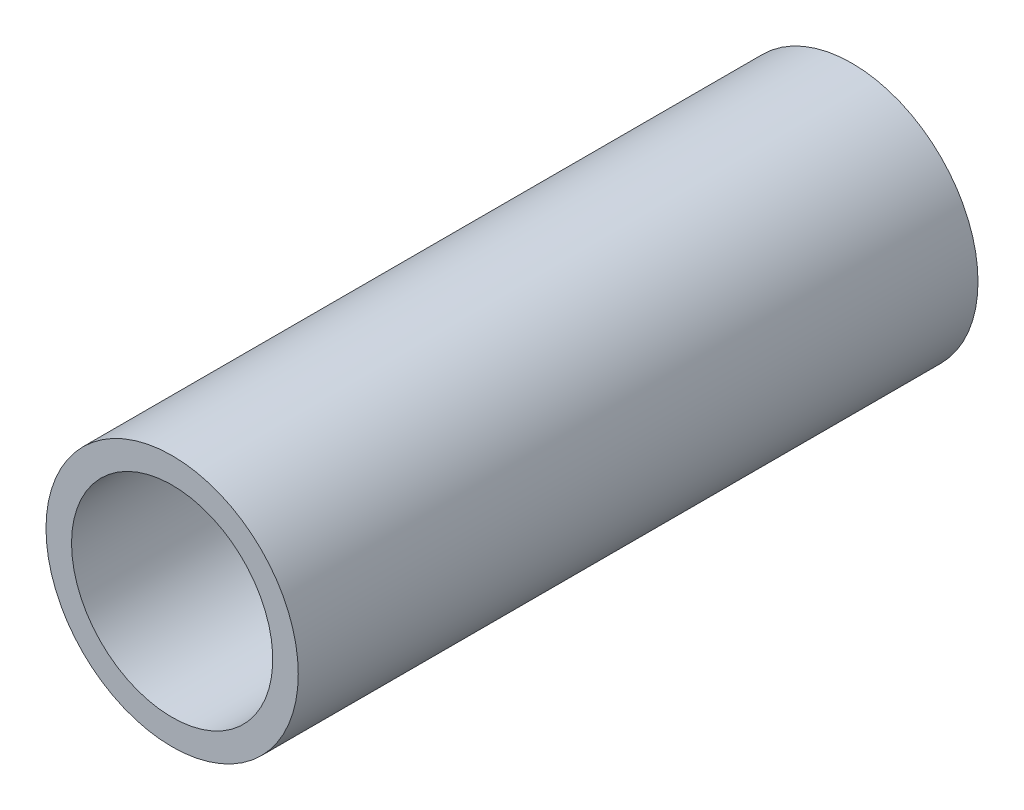
SolidWorks part; units mm, degrees
ref_plane "Front Plane" through (0, 0, 0) normal (0, 0, 1) x (1, 0, 0)
ref_plane "Top Plane" through (0, 0, 0) normal (0, 1, 0) x (1, 0, 0)
ref_plane "Right Plane" through (0, 0, 0) normal (1, 0, 0) x (0, 0, -1)
sketch "Sketch1" plane through (0, 0, 0) normal (0, 0, 1) x (1, 0, 0)
  circle A0 centre (0, 0) radius 16.7005
  dimension "Pipe OD" = 33.401
extrude "Extrude-Thin1" add sketch "Sketch1" along normal mid plane 90 thin thin type one direction reverse wall 3.3782
